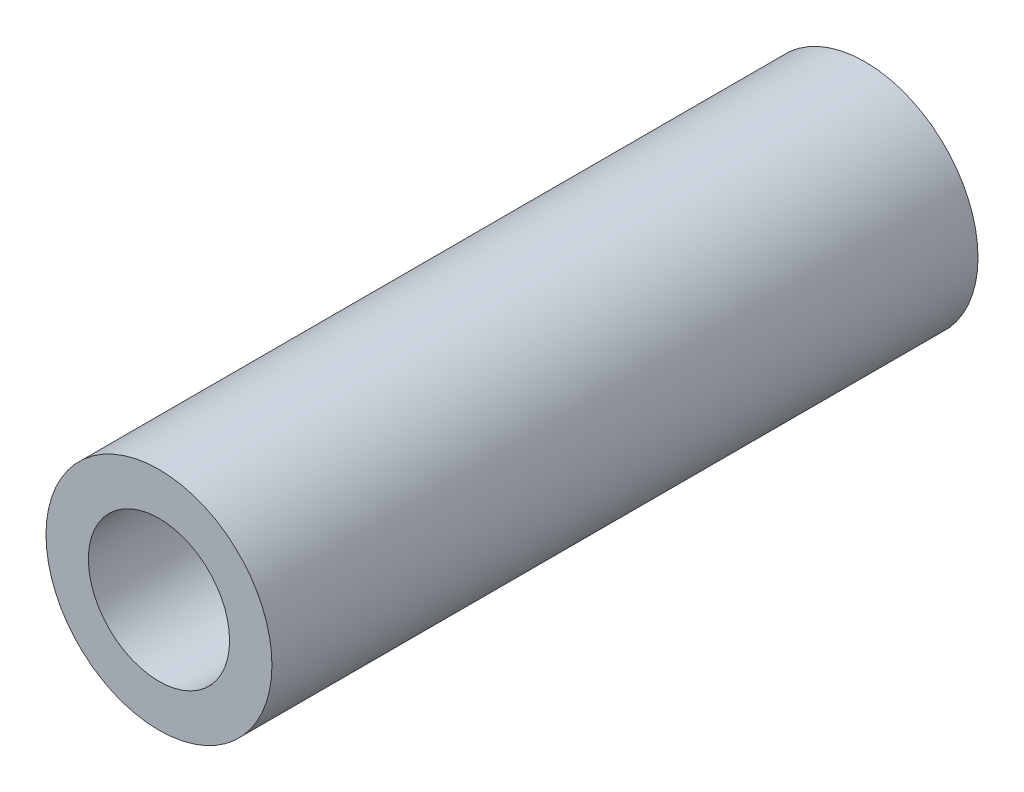
SolidWorks part; units mm, degrees
ref_plane "前视基准面" through (0, 0, 0) normal (0, 0, 1) x (1, 0, 0)
ref_plane "上视基准面" through (0, 0, 0) normal (0, 1, 0) x (1, 0, 0)
ref_plane "右视基准面" through (0, 0, 0) normal (1, 0, 0) x (0, 0, -1)
sketch "草图1" plane through (0, 0, 0) normal (0, 0, 1) x (1, 0, 0)
  circle A0 centre (0, 0) radius 4
  circle A1 centre (0, 0) radius 2.5
  dimension "D1" = 5
  dimension "D2" = 8
extrude "凸台-拉伸1" add sketch "草图1" along normal mid plane 25
